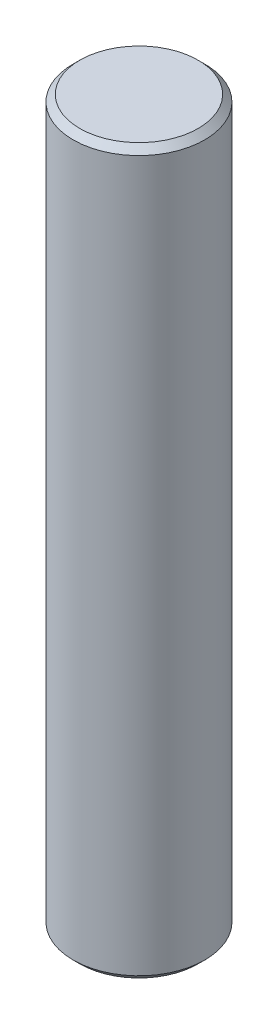
SolidWorks part; units mm, degrees
ref_plane "前视基准面" through (0, 0, 0) normal (0, 0, 1) x (1, 0, 0)
ref_plane "上视基准面" through (0, 0, 0) normal (0, 1, 0) x (1, 0, 0)
ref_plane "右视基准面" through (0, 0, 0) normal (1, 0, 0) x (0, 0, -1)
sketch "草图1" plane through (0, 0, 0) normal (0, 1, 0) x (1, 0, 0)
  circle A0 centre (0, 0) radius 5
  dimension "D1" = 10
extrude "凸台-拉伸1" add sketch "草图1" along normal mid plane 55 contours A0
chamfer "倒角1" distance 0.5 angle 45 2 edges at (0, -27.5, 5) (0, 27.5, 5)
